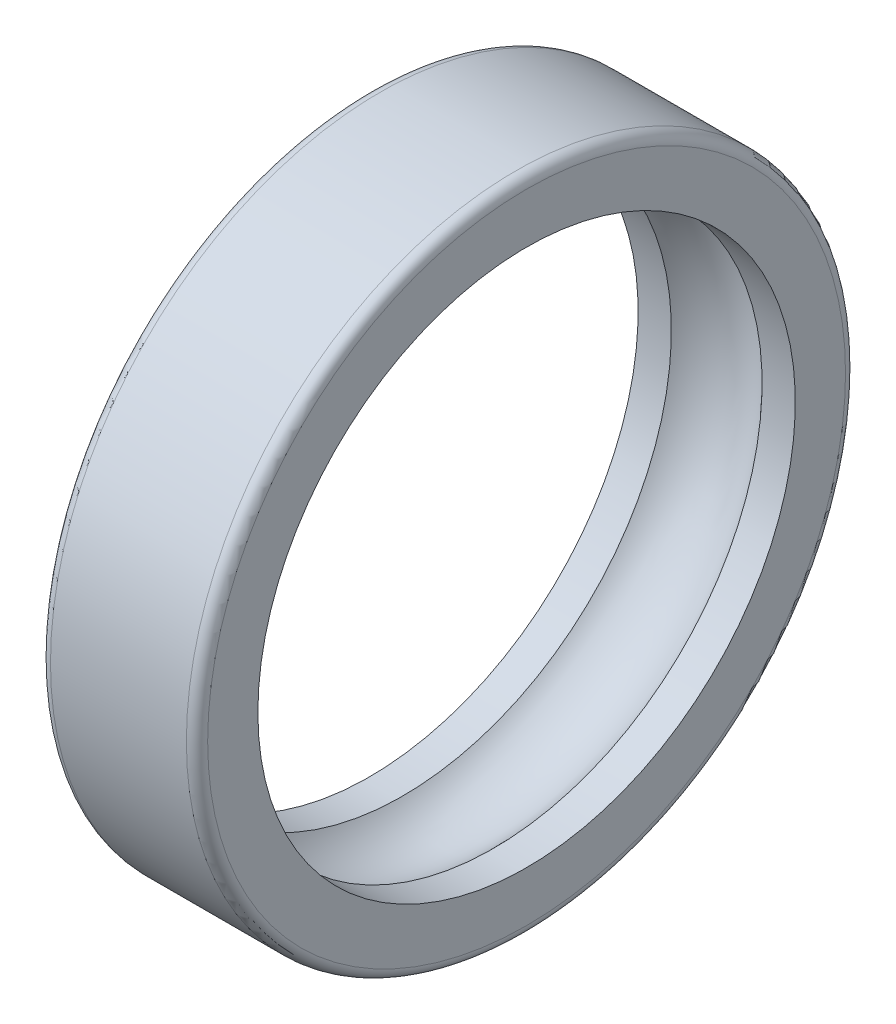
SolidWorks part; units mm, degrees
ref_plane "Front Plane" through (0, 0, 0) normal (0, 0, 1) x (1, 0, 0)
ref_plane "Top Plane" through (0, 0, 0) normal (0, 1, 0) x (1, 0, 0)
ref_plane "Right Plane" through (0, 0, 0) normal (1, 0, 0) x (0, 0, -1)
sketch "Sketch1" plane through (0, 0, 0) normal (0, 0, 1) x (1, 0, 0)
  line L0 (-15.532, 0) -> (46.532, 0) construction
  line L1 (0, 53) -> (0, 0) construction
  line L2 (-15.5, 53) -> (-8.9443, 53)
  line L3 (-15.5, 53) -> (-15.5, 65)
  line L4 (-15.5, 65) -> (15.5, 65)
  line L5 (15.5, 53) -> (15.5, 65)
  line L6 (-15.5, 53) -> (15.5, 65) construction
  line L7 (-15.5, 65) -> (15.5, 53) construction
  line L8 (8.9443, 53) -> (15.5, 53)
  arc A0 (-8.9443, 53) -> (8.9443, 53) centre (0, 45) cw
  point P3 (0, 59)
  dimension "D5" = 12
  dimension "D1" = 31
  dimension "D2" = 65
  dimension "D3" = 53
  dimension "D4" = 8
revolve "Revolve1" add sketch "Sketch1" angle 360 about L0
fillet "Fillet1" radius 2.1 2 edges at (15.5, 0, 65) (-15.5, 0, 65)
